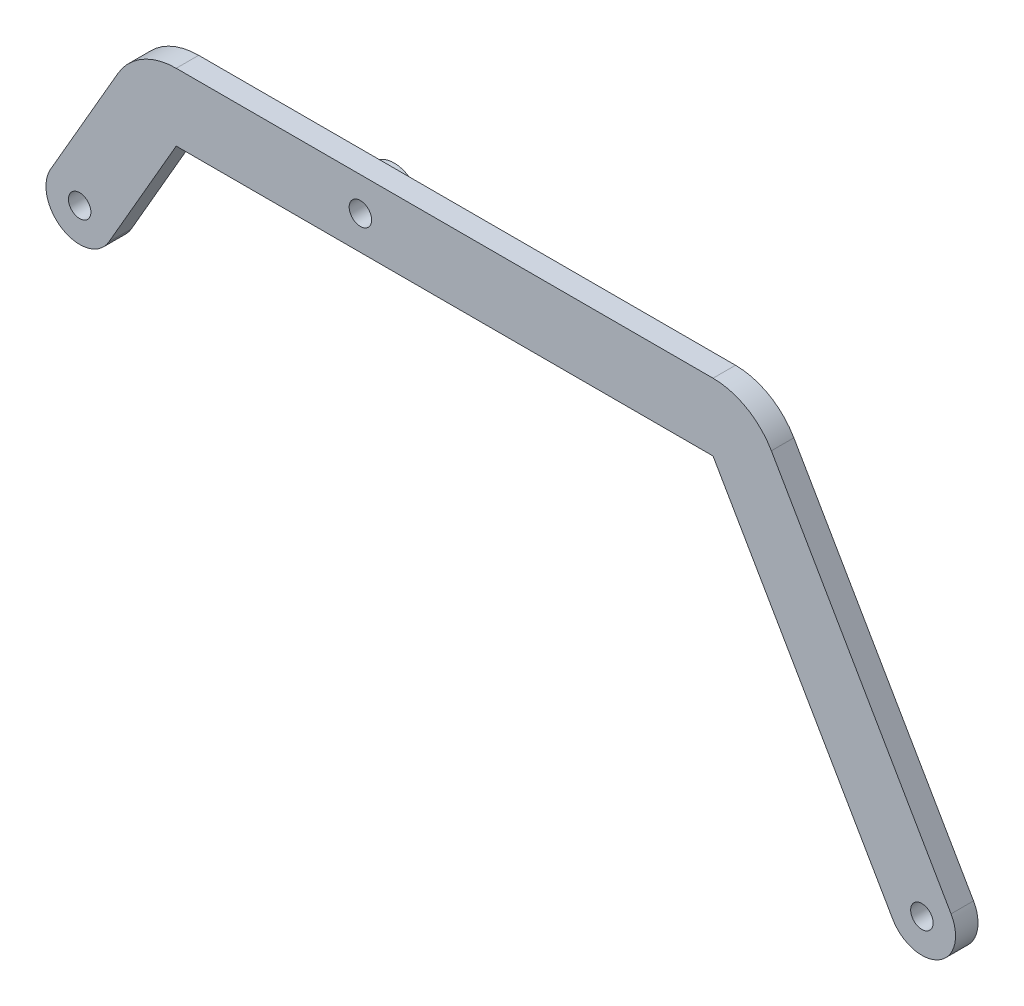
SolidWorks part; units mm, degrees
ref_plane "Front Plane" through (0, 0, 0) normal (0, 0, 1) x (1, 0, 0)
ref_plane "Top Plane" through (0, 0, 0) normal (0, 1, 0) x (1, 0, 0)
ref_plane "Right Plane" through (0, 0, 0) normal (1, 0, 0) x (0, 0, -1)
sketch "Sketch1" plane through (0, 0, 0) normal (0, 0, 1) x (1, 0, 0)
  line L0 (0, -15) -> (0, 15) construction
  line L4 (-82.0096, -15) -> (-112.0096, -66.9615)
  line L6 (-137.9904, -51.9615) -> (-107.9904, 0)
  line L7 (262.9904, -138.5641) -> (182.9904, 0)
  line L9 (157.0096, -15) -> (237.0096, -153.5641)
  line L10 (0, 15) -> (157.0096, 15)
  line L11 (0, -15) -> (157.0096, -15)
  line L12 (0, 15) -> (-82.0096, 15)
  line L13 (0, -15) -> (-82.0096, -15)
  line L14 (237.0096, -153.5641) -> (262.9904, -138.5641) construction
  line L15 (-137.9904, -51.9615) -> (-112.0096, -66.9615) construction
  arc A1 (-107.9904, 0) -> (-82.0096, 15) centre (-82.0096, -15) cw
  arc A2 (182.9904, 0) -> (157.0096, 15) centre (157.0096, -15) ccw
  arc A6 (237.0096, -153.5641) -> (262.9904, -138.5641) centre (250, -146.0641) ccw
  arc A7 (-137.9904, -51.9615) -> (-112.0096, -66.9615) centre (-125, -59.4615) ccw
  point P4 (0, 0)
  point P7 (0, -15)
  point P20 (0, 15)
  dimension "D2" = 60
  dimension "D1" = 30
  dimension "D3" = 250
  dimension "D4" = 160
  dimension "D5" = 125
extrude "Boss-Extrude1" add sketch "Sketch1" along normal blind 10
sketch "Sketch2" plane through (0, 0, 10) normal (0, 0, 1) x (1, 0, 0)
  circle A0 centre (-125, -59.4615) radius 5
  circle A1 centre (250, -146.0641) radius 5
  circle A2 centre (0, 0) radius 5
  dimension "D1" = 10
extrude "Cut-Extrude1" cut sketch "Sketch2" against normal up to surface (10 mm away) up to face at (47.5, -43.007, 0)
sketch "Sketch3" plane through (0, 0, 0) normal (0, 0, -1) x (-1, 0, 0)
  circle A0 centre (0, 0) radius 12
extrude "Boss-Extrude2" add sketch "Sketch3" along normal blind 5
